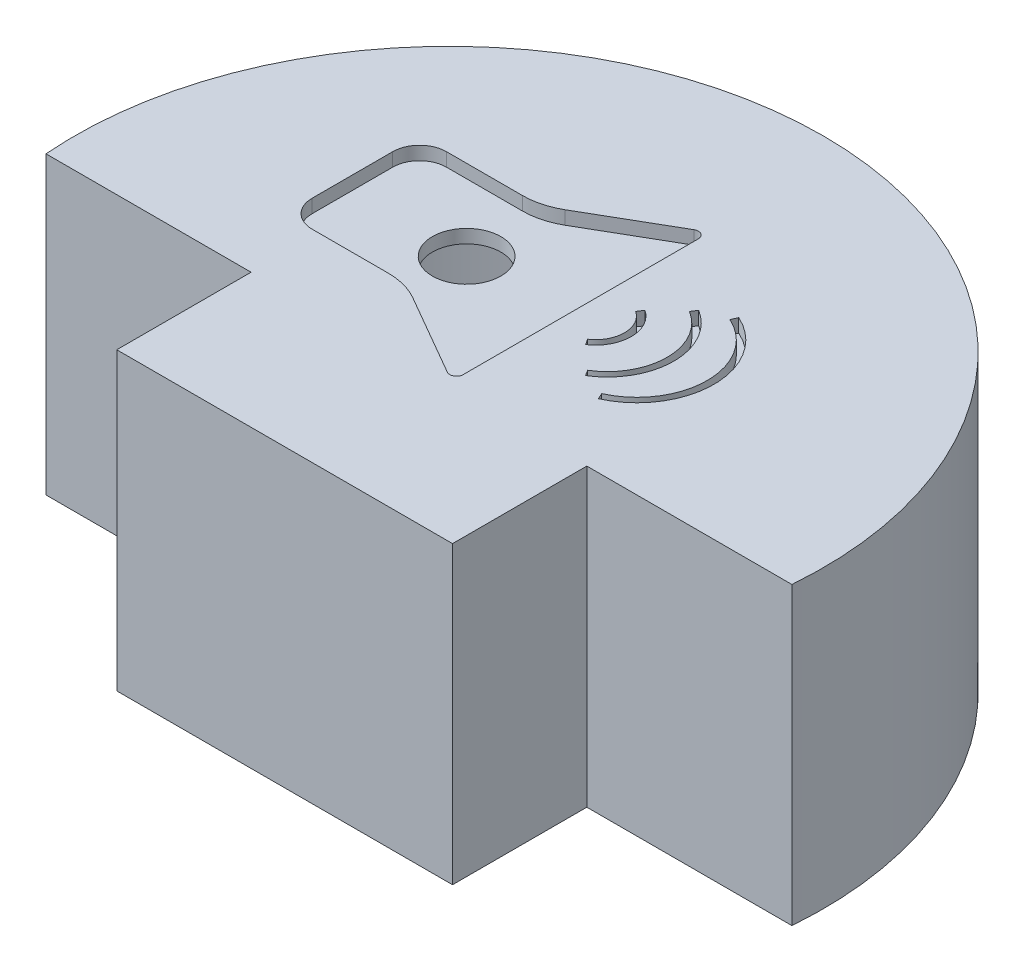
SolidWorks part; units mm, degrees
ref_plane "Alzado" through (0, 0, 0) normal (0, 0, 1) x (1, 0, 0)
ref_plane "Planta" through (0, 0, 0) normal (0, 1, 0) x (1, 0, 0)
ref_plane "Vista lateral" through (0, 0, 0) normal (1, 0, 0) x (0, 0, -1)
sketch "Croquis1" plane through (0, 0, 0) normal (0, 1, 0) x (1, 0, 0)
  line L0 (0, 0) -> (0, 40.0976) construction
  line L1 (-12.5, 0) -> (12.5, 0)
  line L2 (-12.5, 0) -> (-12.5, 10)
  line L3 (12.5, 0) -> (12.5, 10)
  line L4 (-12.5, 10) -> (-27.77, 10)
  line L5 (12.5, 10) -> (27.77, 10)
  arc A0 (-27.77, 10) -> (27.77, 10) centre (0, 12.2376) cw
  point P10 (0, 40.0976)
  dimension "D4" = 27.86
  dimension "D1" = 25
  dimension "D2" = 10
  dimension "D3" = 15.27
extrude "Extruir-Lámina1" add sketch "Croquis1" along normal blind 20 thin thin type one direction reverse wall 2
sketch "Croquis2" plane through (0, 20, 0) normal (0, 1, 0) x (1, 0, 0)
  line L0 (12.5, 10) -> (27.77, 10) construction
  line L1 (12.5, 0) -> (12.5, 10) construction
  line L2 (-12.5, 0) -> (12.5, 0) construction
  line L3 (-12.5, 10) -> (-12.5, 0) construction
  line L4 (-27.77, 10) -> (-12.5, 10) construction
  line L5 (12.5, 10) -> (27.77, 10)
  line L6 (12.5, 0) -> (12.5, 10)
  line L7 (-12.5, 0) -> (12.5, 0)
  line L8 (-12.5, 10) -> (-12.5, 0)
  line L9 (-27.77, 10) -> (-12.5, 10)
  arc A0 (27.77, 10) -> (-27.77, 10) centre (0, 12.2376) ccw construction
  arc A1 (27.77, 10) -> (-27.77, 10) centre (0, 12.2376) ccw
extrude "Saliente-Extruir1" add sketch "Croquis2" along normal blind 2
sketch "Croquis3" plane through (0, 22, 0) normal (0, 1, 0) x (1, 0, 0)
  line L0 (0, 0) -> (0, 40.0976) construction
  line L1 (-14.7383, 20.0488) -> (14.7383, 20.0488) construction
  line L2 (-15, 23.0488) -> (-15, 17.0488)
  line L3 (-13, 25.0488) -> (-7.3397, 25.0488)
  line L4 (-4.8397, 25.7187) -> (1.25, 29.2346)
  line L5 (-4.8397, 14.3789) -> (1.25, 10.863)
  line L6 (-13, 15.0488) -> (-7.3397, 15.0488)
  line L7 (2, 28.8016) -> (2, 11.296)
  arc A0 (27.77, 10) -> (-27.77, 10) centre (0, 12.2376) ccw construction
  arc A1 (-15, 17.0488) -> (-13, 15.0488) centre (-13, 17.0488) ccw
  arc A2 (-15, 23.0488) -> (-13, 25.0488) centre (-13, 23.0488) cw
  arc A3 (-4.8397, 14.3789) -> (-7.3397, 15.0488) centre (-7.3397, 10.0488) ccw
  arc A4 (-7.3397, 25.0488) -> (-4.8397, 25.7187) centre (-7.3397, 30.0488) ccw
  arc A5 (1.25, 10.863) -> (2, 11.296) centre (1.5, 11.296) ccw
  arc A6 (1.25, 29.2346) -> (2, 28.8016) centre (1.5, 28.8016) cw
  point P8 (0, 20.0488)
  point P17 (-15, 15.0488)
  point P20 (-15, 25.0488)
  point P23 (-6, 15.0488)
  point P26 (-6, 25.0488)
  point P29 (2, 10.43)
  point P32 (2, 29.6676)
  dimension "D2" = 2
  dimension "D7" = 5
  dimension "D8" = 0.5
  dimension "D1" = 5
  dimension "D3" = 9
  dimension "D4" = 210
  dimension "D5" = 8
  dimension "D6" = 15
extrude "Cortar-Extruir1" cut sketch "Croquis3" against normal blind 1
sketch "Croquis4" plane through (0, 22, 0) normal (0, 1, 0) x (1, 0, 0)
  line L0 (4, 19.9985) -> (8.73, 19.9985) construction
  line L1 (4.4826, 21.9985) -> (4.4826, 17.9985) construction
  line L2 (6.4826, 23.9985) -> (6.4826, 15.9985) construction
  line L3 (8.73, 19.9985) -> (11.7176, 19.9985) construction
  line L4 (8.4826, 24.9985) -> (8.4826, 14.9985) construction
  line L5 (2, 11.296) -> (2, 28.8016) construction
  arc A0 (4.4826, 21.9985) -> (4.4826, 17.9985) centre (3.1584, 19.9985) cw
  arc A1 (6.4826, 23.9985) -> (6.4826, 15.9985) centre (4.0465, 19.9985) cw
  arc A2 (8.4826, 24.9985) -> (8.4826, 14.9985) centre (6.2362, 19.9985) cw
  point P11 (2, 20.0488)
  dimension "D7" = 4.6834
  dimension "D1" = 4
  dimension "D2" = 8
  dimension "D3" = 10
  dimension "D6" = 2
extrude "Cortar-Extruir-Lámina2" cut sketch "Croquis4" against normal blind 1 thin thin type mid plane wall 0.5
sketch "Croquis7" plane through (0, 22, 0) normal (0, 1, 0) x (1, 0, 0)
  line L0 (-15, 20.0488) -> (2, 20.0488) construction
  line L1 (-15, 23.0488) -> (-15, 17.0488) construction
  line L2 (2, 11.296) -> (2, 28.8016) construction
  circle A0 centre (-6.5, 20.0488) radius 2.55
  dimension "D1" = 5.1
extrude "Cortar-Extruir2" cut sketch "Croquis7" against normal blind 11
ref_plane "Plano1" through (0, 4.9, 0) normal (0, -1, 0) x (-1, 0, 0)
sketch "Croquis9" plane through (0, 4.9, 0) normal (0, -1, 0) x (-1, 0, 0)
  line L23 (-9.5, 3) -> (9.5, 3)
  line L24 (9.5, 3) -> (9.5, 13)
  line L25 (9.5, 13) -> (24.8483, 13)
  line L26 (-24.8483, 13) -> (-9.5, 13)
  line L27 (-9.5, 13) -> (-9.5, 3)
  line L28 (-9.5, 3) -> (9.5, 3)
  line L29 (9.5, 3) -> (9.5, 13)
  line L30 (9.5, 13) -> (24.8483, 13)
  line L31 (-24.8483, 13) -> (-9.5, 13)
  line L32 (-9.5, 13) -> (-9.5, 3)
  arc A7 (24.8483, 13) -> (-24.8483, 13) centre (0, 12.2376) ccw
  arc A8 (24.8483, 13) -> (-24.8483, 13) centre (0, 12.2376) ccw
  dimension "D1" = 1
extrude "Extruir-Lámina2" add sketch "Croquis9" along normal blind 2.5 separate body thin thin type mid plane wall 2.5
